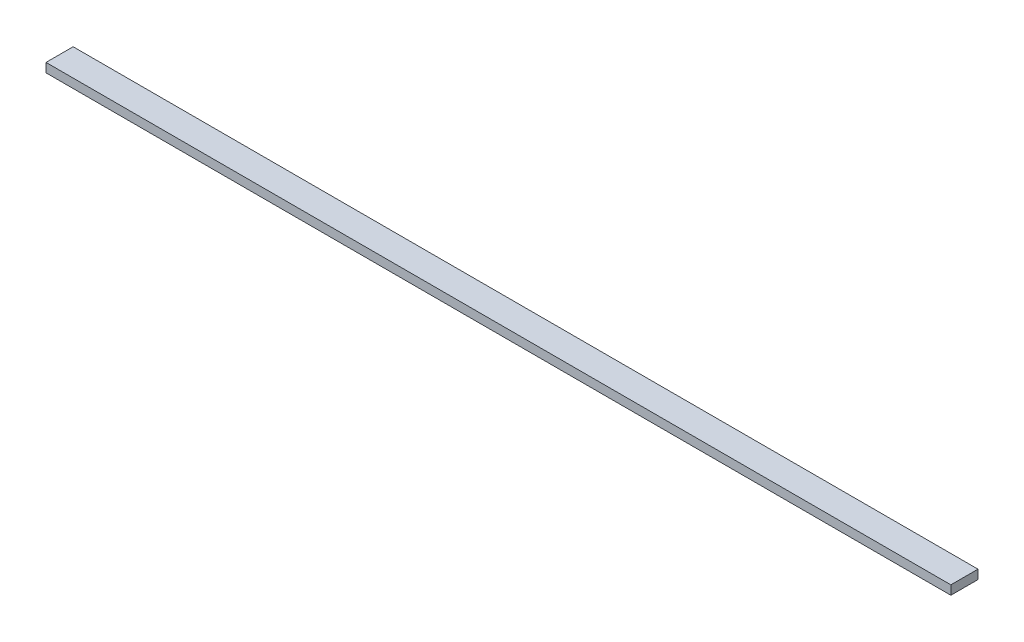
SolidWorks part; units mm, degrees
material "Acrylic (Medium-high impact)"
ref_plane "Front Plane" through (0, 0, 0) normal (0, 0, 1) x (1, 0, 0)
ref_plane "Top Plane" through (0, 0, 0) normal (0, 1, 0) x (1, 0, 0)
ref_plane "Right Plane" through (0, 0, 0) normal (1, 0, 0) x (0, 0, -1)
sketch "Sketch1" plane through (0, 0, 0) normal (0, 1, 0) x (1, 0, 0)
  line L1 (-60.6803, -0.3673) -> (539.3197, -0.3673)
  line L2 (-60.6803, -0.3673) -> (-60.6803, -18.3673)
  line L3 (-60.6803, -18.3673) -> (539.3197, -18.3673)
  line L4 (539.3197, -0.3673) -> (539.3197, -18.3673)
  dimension "D1" = 18
  dimension "D2" = 600
extrude "Boss-Extrude1" add sketch "Sketch1" along normal blind 6
